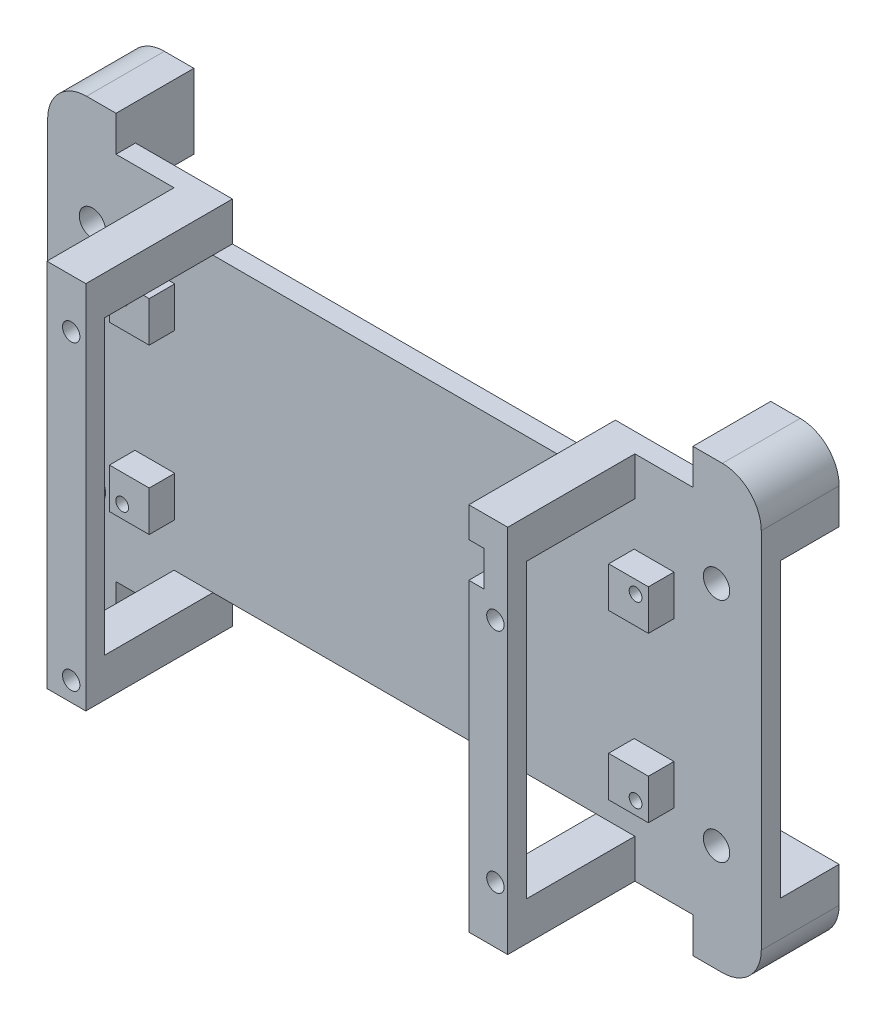
SolidWorks part; units mm, degrees
ref_plane "Front Plane" through (0, 0, 0) normal (0, 0, 1) x (1, 0, 0)
ref_plane "Top Plane" through (0, 0, 0) normal (0, 1, 0) x (1, 0, 0)
ref_plane "Right Plane" through (0, 0, 0) normal (1, 0, 0) x (0, 0, -1)
sketch "Sketch1" plane through (0, 0, 0) normal (0, 0, 1) x (1, 0, 0)
  line L0 (-56.4642, 28.6075) -> (-56.4642, 43.18)
  line L1 (62.23, -43.18) -> (56.4642, -43.18)
  line L2 (69.85, -35.56) -> (69.85, 35.56)
  line L3 (62.23, 43.18) -> (56.4642, 43.18)
  line L4 (-69.85, -35.56) -> (-69.85, 35.56)
  line L5 (69.85, -43.18) -> (-69.85, 43.18) construction
  line L6 (69.85, 43.18) -> (-69.85, -43.18) construction
  line L7 (56.4642, -28.6075) -> (-56.4642, -28.6075)
  line L8 (56.4642, -28.6075) -> (56.4642, 28.6075)
  line L9 (56.4642, 28.6075) -> (-56.4642, 28.6075)
  line L10 (-56.4642, -28.6075) -> (-56.4642, 28.6075)
  line L11 (56.4642, -28.6075) -> (-56.4642, 28.6075) construction
  line L12 (56.4642, 28.6075) -> (-56.4642, -28.6075) construction
  line L13 (-56.4642, -28.6075) -> (-56.4642, -43.18)
  line L14 (56.4642, -28.6075) -> (56.4642, -43.18)
  line L15 (56.4642, 28.6075) -> (56.4642, 43.18)
  line L16 (-56.4642, 43.18) -> (-62.23, 43.18)
  line L17 (-56.4642, -43.18) -> (-62.23, -43.18)
  arc A0 (-62.23, 43.18) -> (-69.85, 35.56) centre (-62.23, 35.56) ccw
  arc A1 (69.85, 35.56) -> (62.23, 43.18) centre (62.23, 35.56) ccw
  arc A2 (62.23, -43.18) -> (69.85, -35.56) centre (62.23, -35.56) ccw
  arc A3 (-62.23, -43.18) -> (-69.85, -35.56) centre (-62.23, -35.56) cw
  point P0 (0, 0)
  point P6 (0, 0)
  dimension "D4" = 7.62
  dimension "D5" = 7.62
  dimension "D6" = 7.62
  dimension "D7" = 7.62
  dimension "D1" = 139.7
  dimension "D2" = 86.36
  dimension "D3" = 13.3858
extrude "Boss-Extrude1" add sketch "Sketch1" along normal blind 3.81 contours L17 L13 L10 L0 L16 L4 | L15 L8 L14 L1 L2 L3 | L10 L7 L8 L9
sketch "Sketch2" plane through (0, 0, 0) normal (0, 0, -1) x (-1, 0, 0)
  line L0 (0, 0) -> (0, 50000) construction
  line L17 (-62.23, 43.18) -> (-56.4642, 43.18)
  line L18 (-69.85, 35.56) -> (-69.85, 28.6075)
  line L19 (-69.85, 28.6075) -> (-56.4642, 28.6075)
  line L20 (-56.4642, 43.18) -> (-56.4642, 28.6075)
  line L21 (0, 0) -> (50000, 0) construction
  line L22 (69.85, 28.6075) -> (56.4642, 28.6075)
  line L23 (56.4642, 43.18) -> (56.4642, 28.6075)
  line L24 (62.23, 43.18) -> (56.4642, 43.18)
  line L25 (69.85, 35.56) -> (69.85, 28.6075)
  line L26 (69.85, -35.56) -> (69.85, -28.6075)
  line L27 (62.23, -43.18) -> (56.4642, -43.18)
  line L28 (56.4642, -43.18) -> (56.4642, -28.6075)
  line L29 (69.85, -28.6075) -> (56.4642, -28.6075)
  line L30 (-69.85, -28.6075) -> (-56.4642, -28.6075)
  line L31 (-56.4642, -43.18) -> (-56.4642, -28.6075)
  line L32 (-62.23, -43.18) -> (-56.4642, -43.18)
  line L33 (-69.85, -35.56) -> (-69.85, -28.6075)
  arc A4 (-62.23, 43.18) -> (-69.85, 35.56) centre (-62.23, 35.56) ccw
  arc A5 (62.23, 43.18) -> (69.85, 35.56) centre (62.23, 35.56) cw
  arc A6 (69.85, -35.56) -> (62.23, -43.18) centre (62.23, -35.56) cw
  arc A7 (-62.23, -43.18) -> (-69.85, -35.56) centre (-62.23, -35.56) cw
  point P26 (-66.294, 43.18)
  point P29 (66.294, 43.18)
  point P32 (66.294, -43.18)
  point P33 (-69.85, 43.18)
  point P35 (-66.294, -43.18)
  point P39 (69.85, 43.18)
  point P42 (69.85, -43.18)
  point P45 (-69.85, -43.18)
  dimension "D1" = 7.62
  dimension "D2" = 7.62
  dimension "D3" = 7.62
  dimension "D4" = 7.62
extrude "Boss-Extrude2" add sketch "Sketch2" along normal blind 11.43
sketch "Sketch3" plane through (0, 0, 3.81) normal (0, 0, 1) x (1, 0, 0)
  circle A0 centre (-61.0842, 22.2292) radius 2.58
  circle A1 centre (-61.0842, -22.2208) radius 2.58
  circle A2 centre (61.0958, -22.2208) radius 2.58
  circle A3 centre (61.0958, 22.2292) radius 2.58
extrude "Cut-Extrude1" cut sketch "Sketch3" against normal up to next
sketch "Sketch4" plane through (0, 0, 3.81) normal (0, 0, 1) x (1, 0, 0)
  line L0 (-56.4642, 28.6075) -> (56.4642, -28.6075) construction
  line L1 (-56.4642, -28.6075) -> (56.4642, 28.6075) construction
  line L2 (0, 0) -> (0, 50000) construction
  line L3 (52.7558, -20.0025) -> (-52.7558, -20.0025)
  line L4 (52.7558, -20.0025) -> (52.7558, -12.1068)
  line L5 (52.7558, 20.0025) -> (39.4801, 20.0025)
  line L6 (-52.7558, -20.0025) -> (-52.7558, -12.1068)
  line L7 (52.7558, -20.0025) -> (-52.7558, 20.0025) construction
  line L8 (52.7558, 20.0025) -> (-52.7558, -20.0025) construction
  line L9 (52.7558, 20.0025) -> (44.969, 20.0025)
  line L10 (52.7558, 20.0025) -> (52.7558, 12.1068)
  line L11 (52.7558, 12.1068) -> (44.969, 12.1068)
  line L12 (44.969, 20.0025) -> (44.969, 12.1068)
  line L13 (0, 0) -> (50000, 0) construction
  line L14 (-44.969, 20.0025) -> (-44.969, 12.1068)
  line L15 (-52.7558, 12.1068) -> (-44.969, 12.1068)
  line L16 (-52.7558, 20.0025) -> (-52.7558, 12.1068)
  line L17 (-52.7558, 20.0025) -> (-44.969, 20.0025)
  line L18 (-52.7558, -20.0025) -> (-44.969, -20.0025)
  line L19 (-52.7558, -20.0025) -> (-52.7558, -12.1068)
  line L20 (-52.7558, -12.1068) -> (-44.969, -12.1068)
  line L21 (-44.969, -20.0025) -> (-44.969, -12.1068)
  line L22 (44.969, -20.0025) -> (44.969, -12.1068)
  line L23 (52.7558, -12.1068) -> (44.969, -12.1068)
  line L24 (52.7558, -20.0025) -> (52.7558, -12.1068)
  line L25 (52.7558, -20.0025) -> (44.969, -20.0025)
  line L26 (-39.4801, 20.0025) -> (-52.7558, 20.0025)
  line L27 (-52.7558, 12.1068) -> (-52.7558, 20.0025)
  point P8 (0, 0)
  dimension "D1" = 40.005
  dimension "D2" = 105.5116
extrude "Boss-Extrude3" add sketch "Sketch4" along normal blind 5 contours L17 L16 L15 L14 | L5 L12 L11 L10 | L4 L23 L22 L3 | L3 L21 L20 L6
sketch "Sketch5" plane through (0, 0, 8.81) normal (0, 0, 1) x (1, 0, 0)
  circle A0 centre (50.2442, 17.5025) radius 1.25
  circle A1 centre (50.2442, -17.4975) radius 1.25
  circle A2 centre (-50.2558, -17.4975) radius 1.25
  circle A3 centre (-50.2558, 17.5025) radius 1.25
extrude "Cut-Extrude2" cut sketch "Sketch5" against normal up to next
sketch "Sketch6" plane through (0, 0, 30.8413) normal (0, 0, 1) x (1, 0, 0)
  line L0 (56.4642, 28.6075) -> (-56.4642, 28.6075) construction
  line L6 (0, 28.6075) -> (0, 50028.6075) construction
  line L7 (-0.0058, 0.0025) -> (-50000.0058, 0.0025) construction
  point P6 (0, 28.6075)
sketch "Sketch7" plane through (0, 0, 3.81) normal (0, 0, 1) x (1, 0, 0)
  line L5 (-0.0058, 0.0025) -> (4.82, 50000.0023) construction
  line L7 (-0.0058, 0.0025) -> (49999.9942, 0.0025) construction
sketch "Sketch8" plane through (0, 0, 3.81) normal (0, 0, 1) x (1, 0, 0)
  line L0 (56.4642, 28.6075) -> (-56.4642, 28.6075) construction
  line L1 (-45.1079, 28.6075) -> (-37.4879, 28.6075)
  line L2 (-45.1079, 28.6075) -> (-45.1079, 36.2275)
  line L3 (-45.1079, 36.2275) -> (-37.4879, 36.2275)
  line L4 (-37.4879, 28.6075) -> (-37.4879, 36.2275)
  line L5 (0, -11.132) -> (0, 11.132) construction
  line L6 (45.1079, 36.2275) -> (37.4879, 36.2275)
  line L7 (37.4879, 28.6075) -> (37.4879, 36.2275)
  line L8 (45.1079, 28.6075) -> (37.4879, 28.6075)
  line L9 (45.1079, 28.6075) -> (45.1079, 36.2275)
  line L10 (11.132, 0) -> (-11.132, 0) construction
  line L11 (45.1079, -28.6075) -> (45.1079, -36.2275)
  line L12 (45.1079, -28.6075) -> (37.4879, -28.6075)
  line L13 (37.4879, -28.6075) -> (37.4879, -36.2275)
  line L14 (45.1079, -36.2275) -> (37.4879, -36.2275)
  line L15 (-45.1079, -36.2275) -> (-37.4879, -36.2275)
  line L16 (-37.4879, -28.6075) -> (-37.4879, -36.2275)
  line L17 (-45.1079, -28.6075) -> (-37.4879, -28.6075)
  line L18 (-45.1079, -28.6075) -> (-45.1079, -36.2275)
  dimension "D1" = 7.62
  dimension "D2" = 7.62
extrude "Boss-Extrude4" add sketch "Sketch8" along normal blind 24.892 separate body
sketch "Sketch9" plane through (0, 0, 3.81) normal (0, 0, 1) x (1, 0, 0)
  line L1 (45.1079, 36.2275) -> (37.4879, 36.2275)
  line L2 (45.1079, 36.2275) -> (45.1079, 28.6075)
  line L3 (45.1079, 28.6075) -> (37.4879, 28.6075)
  line L4 (37.4879, 36.2275) -> (37.4879, 28.6075)
  line L5 (-37.4879, 36.2275) -> (-45.1079, 36.2275)
  line L6 (-37.4879, 36.2275) -> (-37.4879, 28.6075)
  line L7 (-37.4879, 28.6075) -> (-45.1079, 28.6075)
  line L8 (-45.1079, 36.2275) -> (-45.1079, 28.6075)
  line L9 (-37.4879, -28.6075) -> (-45.1079, -28.6075)
  line L10 (-37.4879, -28.6075) -> (-37.4879, -36.2275)
  line L11 (-37.4879, -36.2275) -> (-45.1079, -36.2275)
  line L12 (-45.1079, -28.6075) -> (-45.1079, -36.2275)
  line L13 (45.1079, -28.6075) -> (37.4879, -28.6075)
  line L14 (45.1079, -28.6075) -> (45.1079, -36.2275)
  line L15 (45.1079, -36.2275) -> (37.4879, -36.2275)
  line L16 (37.4879, -28.6075) -> (37.4879, -36.2275)
extrude "Boss-Extrude5" add sketch "Sketch9" against normal blind 3.81
sketch "Sketch10" plane through (0, -28.6075, 0) normal (0, 1, 0) x (1, 0, 0)
  line L0 (-45.1079, -28.702) -> (-45.1079, -3.81) construction
  line L1 (-37.4879, -28.702) -> (-45.1079, -28.702)
  line L2 (-37.4879, -28.702) -> (-37.4879, -24.9947)
  line L3 (-37.4879, -24.9947) -> (-45.1079, -24.9947)
  line L4 (-45.1079, -28.702) -> (-45.1079, -24.9947)
  line L5 (37.4879, -28.702) -> (37.4879, -3.81) construction
  line L6 (45.1079, -28.702) -> (37.4879, -28.702)
  line L7 (45.1079, -28.702) -> (45.1079, -24.9947)
  line L8 (45.1079, -24.9947) -> (37.4879, -24.9947)
  line L9 (37.4879, -28.702) -> (37.4879, -24.9947)
extrude "Boss-Extrude6" add sketch "Sketch10" along normal up to next
sketch "Sketch11" plane through (-45.1079, 0, 0) normal (-1, 0, 0) x (0, 0, 1)
  line L1 (3.81, -28.6075) -> (0, -28.6075)
  line L2 (3.81, -28.6075) -> (3.81, -36.2275)
  line L3 (3.81, -36.2275) -> (0, -36.2275)
  line L4 (0, -28.6075) -> (0, -36.2275)
  line L5 (3.81, 28.6075) -> (0, 28.6075)
  line L6 (3.81, 28.6075) -> (3.81, 36.2275)
  line L7 (3.81, 36.2275) -> (0, 36.2275)
  line L8 (0, 28.6075) -> (0, 36.2275)
extrude "Boss-Extrude7" add sketch "Sketch11" along normal up to next
sketch "Sketch12" plane through (45.1079, 0, 0) normal (1, 0, 0) x (0, 0, -1)
  line L1 (-3.81, 28.6075) -> (0, 28.6075)
  line L2 (-3.81, 28.6075) -> (-3.81, 36.2275)
  line L3 (-3.81, 36.2275) -> (0, 36.2275)
  line L4 (0, 28.6075) -> (0, 36.2275)
  line L5 (-3.81, -28.6075) -> (0, -28.6075)
  line L6 (-3.81, -28.6075) -> (-3.81, -36.2275)
  line L7 (-3.81, -36.2275) -> (0, -36.2275)
  line L8 (0, -28.6075) -> (0, -36.2275)
extrude "Boss-Extrude8" add sketch "Sketch12" along normal up to next
ref_plane "Plane1" through (-35.6752, -32.2658, -9.88) normal (-1, 0, 0) x (0, 0, 1)
sketch "Sketch14" plane through (0, 0, 28.702) normal (0, 0, 1) x (1, 0, 0)
  circle A0 centre (-40.3491, 26.6418) radius 1.7018
  circle A1 centre (-40.3491, -32.4452) radius 1.7018
  circle A2 centre (42.6918, 19.2768) radius 1.7018
  circle A3 centre (42.6918, -25.1723) radius 1.7018
  point P5 (41.0719, 19.3316)
extrude "Cut-Extrude3" cut sketch "Sketch14" against normal blind 3.81
ref_plane "Plane2" through (50.0058, 33.7542, -9.48) normal (1, 0, 0) x (0, 0, -1)
sketch "Sketch16" plane through (0, 0, 28.702) normal (0, 0, 1) x (1, 0, 0)
  line L0 (37.4879, 36.2275) -> (37.4879, -36.2275) construction
  line L1 (37.4879, 30.3226) -> (40.4273, 30.3226)
  line L2 (37.4879, 30.3226) -> (37.4879, 23.4292)
  line L3 (37.4879, 23.4292) -> (40.4273, 23.4292)
  line L4 (40.4273, 30.3226) -> (40.4273, 23.4292)
  line L5 (50.8999, 30.3226) -> (27.4049, 30.3226) construction
  line L6 (39.7345, 22.2292) -> (41.1202, 24.6292) construction
extrude "Cut-Extrude4" cut sketch "Sketch16" against normal blind 7.62
